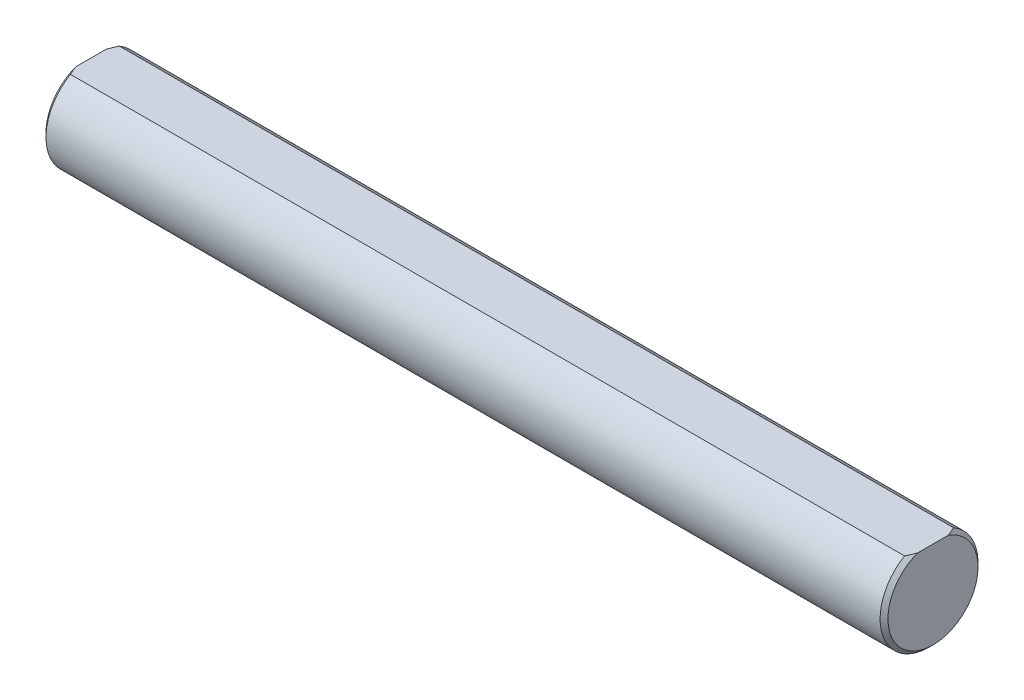
SolidWorks part; units mm, degrees
material "AISI 1045 Steel, cold drawn"
ref_plane "Front Plane" through (0, 0, 0) normal (0, 0, 1) x (1, 0, 0)
ref_plane "Top Plane" through (0, 0, 0) normal (0, 1, 0) x (1, 0, 0)
ref_plane "Right Plane" through (0, 0, 0) normal (1, 0, 0) x (0, 0, -1)
sketch "Sketch1" plane through (0, 0, 0) normal (1, 0, 0) x (0, 0, -1)
  circle A2 centre (0, 0) radius 3.175
  dimension "D1" = 6.35
extrude "Boss-Extrude1" add sketch "Sketch1" along normal blind 54.61
chamfer "Chamfer1" distance 0.254 angle 45 2 edges at (54.61, 0, -3.175) (0, 0, -3.175)
sketch "Sketch2" plane through (54.61, 0, 0) normal (1, 0, 0) x (0, 0, -1)
  line L0 (-1.5875, 2.7496) -> (1.5875, 2.7496)
  circle A0 centre (0, 0) radius 3.175 construction
  arc A1 (1.5875, 2.7496) -> (-1.5875, 2.7496) centre (0, 0) ccw
  dimension "D1" = 3.175
extrude "Cut-Extrude2" cut sketch "Sketch2" against normal through all
